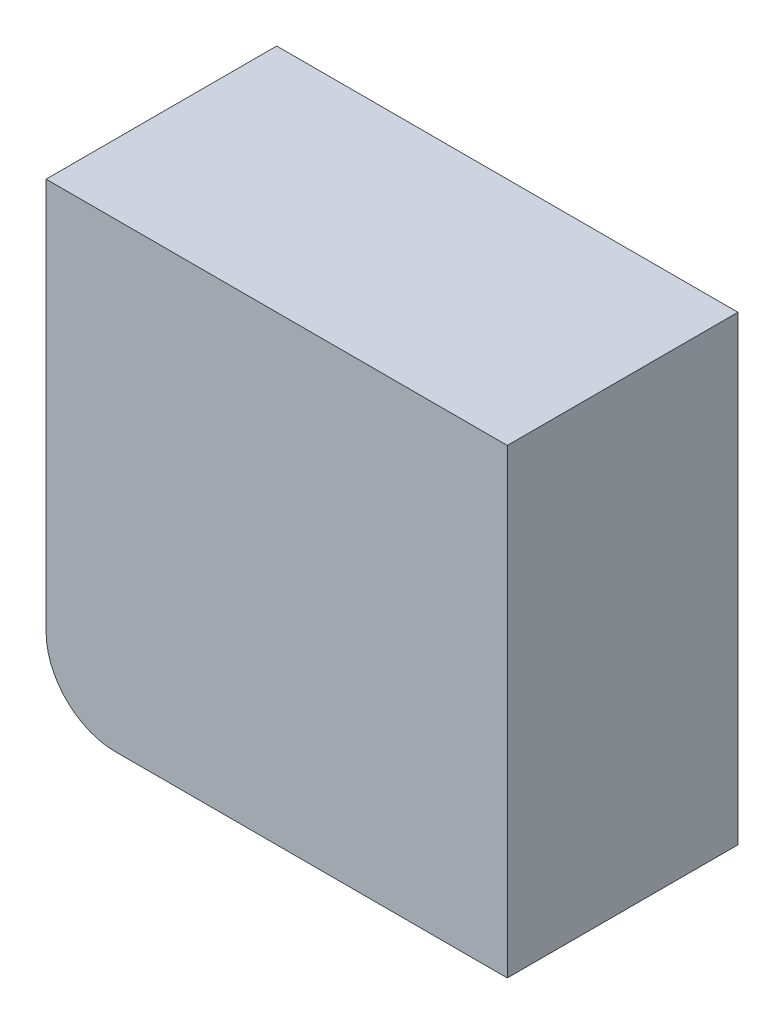
SolidWorks part; units mm, degrees
ref_plane "前视基准面" through (0, 0, 0) normal (0, 0, 1) x (1, 0, 0)
ref_plane "上视基准面" through (0, 0, 0) normal (0, 1, 0) x (1, 0, 0)
ref_plane "右视基准面" through (0, 0, 0) normal (1, 0, 0) x (0, 0, -1)
other "Configuration Table"
sketch "草图1" plane through (0, 0, 0) normal (0, 0, 1) x (1, 0, 0)
  line L1 (0, 0) -> (20, 0)
  line L2 (0, 0) -> (0, 20)
  line L3 (0, 20) -> (20, 20)
  line L4 (20, 0) -> (20, 20)
extrude "BaseBox" add sketch "草图1" along normal blind 10
fillet "FaceFillet" radius 3 1 edges at (0, 0, 5)
